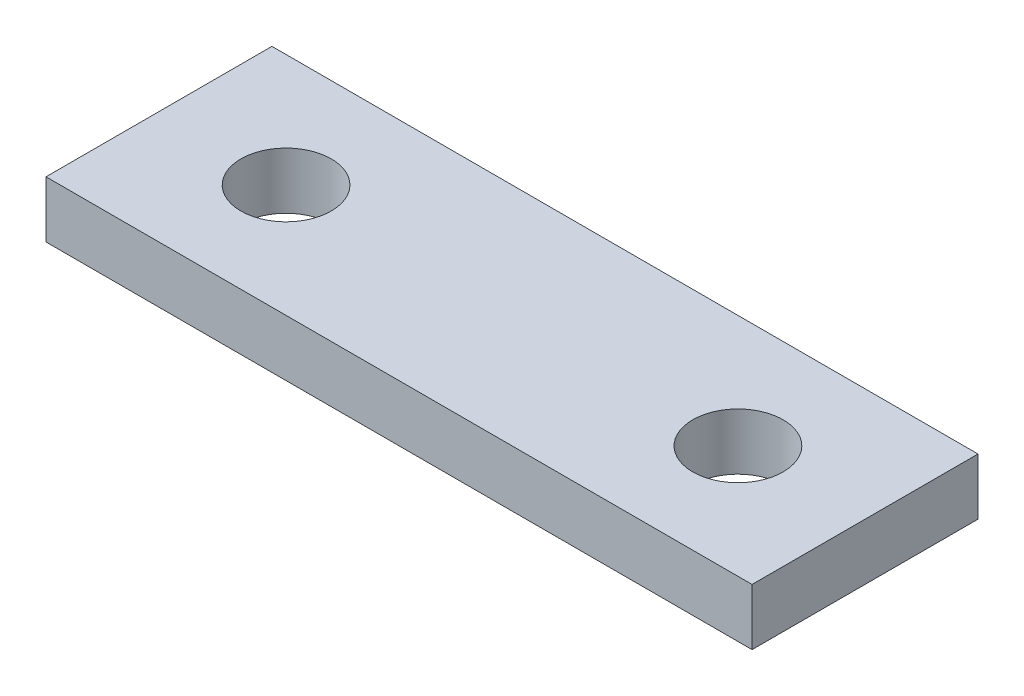
SolidWorks part; units mm, degrees
ref_plane "Front Plane" through (0, 0, 0) normal (0, 0, 1) x (1, 0, 0)
ref_plane "Top Plane" through (0, 0, 0) normal (0, 1, 0) x (1, 0, 0)
ref_plane "Right Plane" through (0, 0, 0) normal (1, 0, 0) x (0, 0, -1)
sketch "Sketch1" plane through (0, 0, 0) normal (0, 1, 0) x (1, 0, 0)
  line L0 (-18.6968, 20) -> (156.0065, 20) construction
  line L1 (0, 0) -> (125, 0)
  line L2 (0, 0) -> (0, 40)
  line L3 (0, 40) -> (125, 40)
  line L4 (125, 0) -> (125, 40)
  circle A0 centre (22.5, 20) radius 8
  circle A1 centre (102.5, 20) radius 8
  dimension "D6" = 16
  dimension "D1" = 125
  dimension "D2" = 40
  dimension "D3" = 20
  dimension "D4" = 80
extrude "Boss-Extrude1" add sketch "Sketch1" along normal blind 10
